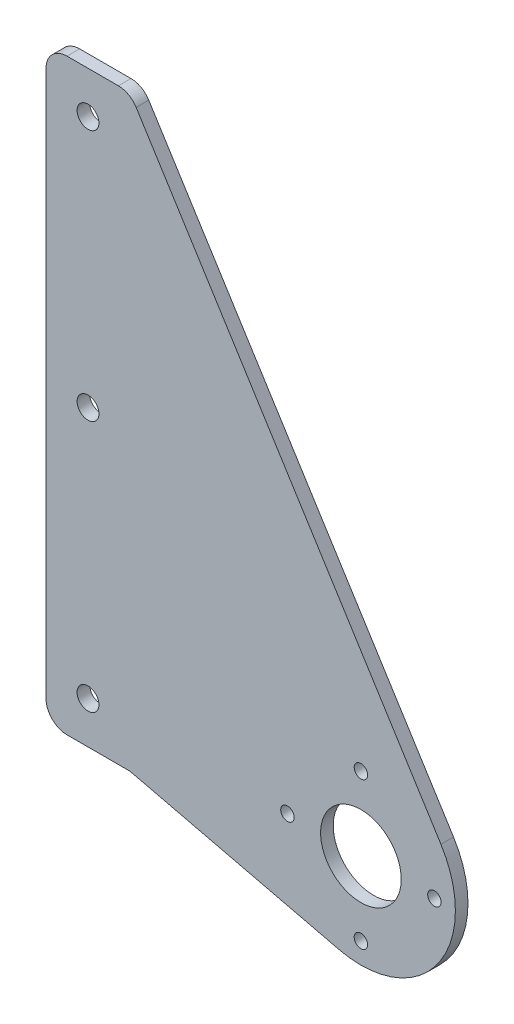
SolidWorks part; units mm, degrees
ref_plane "正面" through (0, 0, 0) normal (0, 0, 1) x (1, 0, 0)
ref_plane "平面" through (0, 0, 0) normal (0, 1, 0) x (1, 0, 0)
ref_plane "右側面" through (0, 0, 0) normal (1, 0, 0) x (0, 0, -1)
sketch "ｽｹｯﾁ2" plane through (0, 0, 0) normal (0, 0, 1) x (1, 0, 0)
  line L0 (17.5, 0) -> (-17.5, 0) construction
  line L1 (0, -17.5) -> (0, 17.5) construction
  line L2 (0, 0) -> (-55, 60) construction
  line L3 (-65, 0) -> (-65, 60) construction
  line L4 (-65, 60) -> (-65, 120) construction
  line L5 (-75, 130) -> (-75, -10)
  line L6 (-75, -10) -> (-55, -10)
  line L7 (-75, 130) -> (-55, 130)
  line L8 (-55, 130) -> (-55, -10) construction
  line L9 (-55, 130) -> (19.0594, 11.9578)
  line L10 (-55, -10) -> (-5.2255, -21.8848)
  line L11 (-75, 60) -> (-55, 60) construction
  line L12 (0, -22.5) -> (-75, -22.5) construction
  line L13 (-75, -22.5) -> (-75, -10) construction
  line L14 (0, -50) -> (-75, -50) construction
  line L15 (-75, -10) -> (-75, -50) construction
  line L16 (-75, -30) -> (-55, -30) construction
  line L17 (-55, -30) -> (-55, -10) construction
  circle A0 centre (0, 0) radius 9.6
  circle A1 centre (0, 17.5) radius 1.6
  circle A2 centre (17.5, 0) radius 1.6
  circle A3 centre (0, -17.5) radius 1.6
  circle A4 centre (-17.5, 0) radius 1.6
  circle A5 centre (-65, 60) radius 2.6
  circle A6 centre (-65, 120) radius 2.6
  circle A7 centre (-65, 0) radius 2.6
  arc A8 (-5.2255, -21.8848) -> (19.0594, 11.9578) centre (0, 0) ccw
  circle A9 centre (0, 0) radius 50 construction
  point P6 (0, 0)
  point P9 (0, 0)
  point P29 (-65, 60)
  dimension "D1" = 19.2
  dimension "D2" = 3.2
  dimension "D3" = 5.2
  dimension "D4" = 60
  dimension "D5" = 60
  dimension "D8" = 22.5
  dimension "D9" = 20
  dimension "D11" = 10
  dimension "D12" = 100
  dimension "D13" = 75
  dimension "D6" = 90
  dimension "D7" = 35
  dimension "D10" = 10
  dimension "D14" = 40
  dimension "D15" = 20
  dimension "D16" = 20
extrude "ﾎﾞｽ - 押し出し1" add sketch "ｽｹｯﾁ2" along normal blind 3
fillet "ﾌｨﾚｯﾄ3" radius 5 4 edges at (-55, 130, 1.5) (-55, -10, 1.5) (-75, -10, 1.5) (-75, 130, 1.5)
